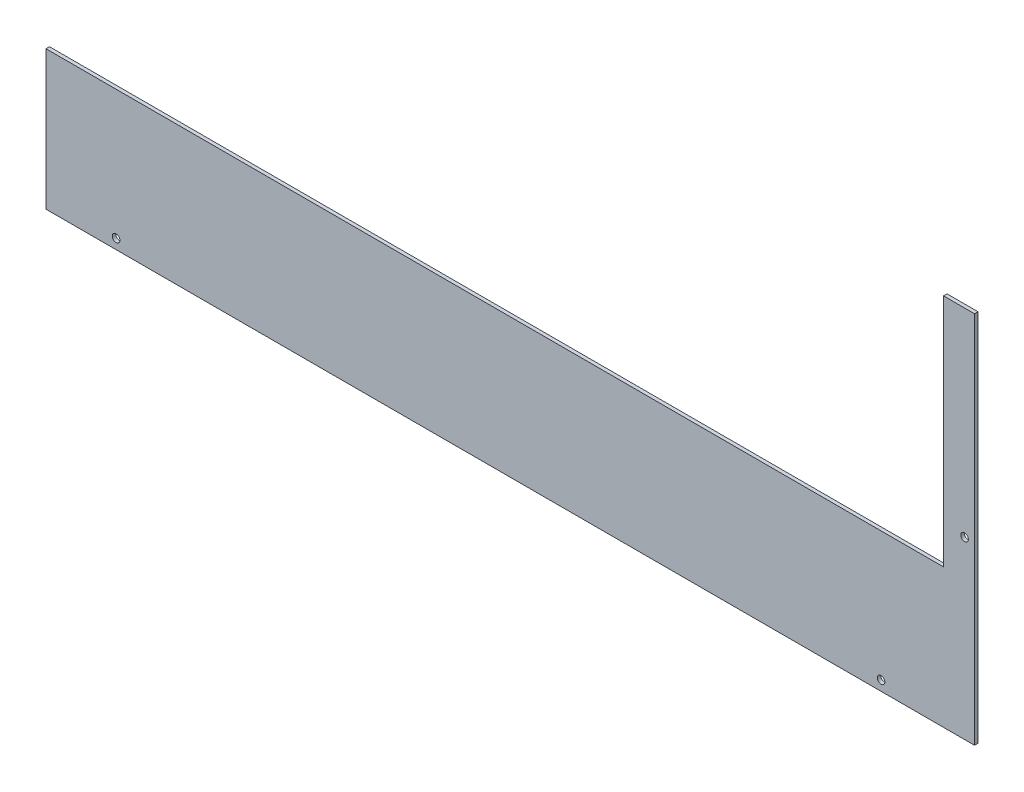
SolidWorks part; units mm, degrees
ref_plane "정면" through (0, 0, 0) normal (0, 0, 1) x (1, 0, 0)
ref_plane "윗면" through (0, 0, 0) normal (0, 1, 0) x (1, 0, 0)
ref_plane "우측면" through (0, 0, 0) normal (1, 0, 0) x (0, 0, -1)
sketch "스케치1" plane through (0, 0, 0) normal (0, 0, 1) x (1, 0, 0)
  line L1 (0, 0) -> (795, 0)
  line L2 (0, 0) -> (0, 119)
  line L3 (0, 119) -> (768.5, 119)
  line L4 (795, 0) -> (795, 320)
  line L5 (795, 320) -> (768.5, 320)
  line L8 (768.5, 320) -> (768.5, 119)
  circle A0 centre (60, 8.5) radius 3.25
  circle A1 centre (715, 8.5) radius 3.25
  circle A2 centre (786.5, 150) radius 3.25
  point P13 (729.5803, 8.5)
  point P14 (0, 0)
  point P15 (768.5, 152.9228)
  dimension "D11" = 6.5
  dimension "D1" = 119
  dimension "D2" = 768.5
  dimension "D3" = 795
  dimension "D4" = 320
  dimension "D5" = 141.5
  dimension "D6" = 8.5
  dimension "D7" = 71.5
  dimension "D8" = 60
  dimension "D9" = 655
  dimension "D10" = 8.5
extrude "보스-돌출1" add sketch "스케치1" along normal blind 3
